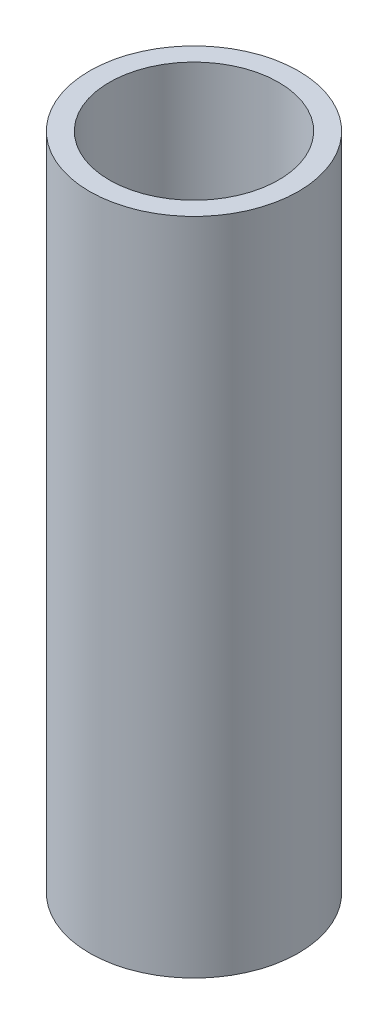
SolidWorks part; units mm, degrees
ref_plane "Front Plane" through (0, 0, 0) normal (0, 0, 1) x (1, 0, 0)
ref_plane "Top Plane" through (0, 0, 0) normal (0, 1, 0) x (1, 0, 0)
ref_plane "Right Plane" through (0, 0, 0) normal (1, 0, 0) x (0, 0, -1)
sketch "Sketch1" plane through (0, 0, 0) normal (0, 1, 0) x (1, 0, 0)
  circle A0 centre (0, 0) radius 2.375
  circle A1 centre (0, 0) radius 1.925
  dimension "D1" = 3.85
  dimension "D2" = 4.75
extrude "Boss-Extrude1" add sketch "Sketch1" along normal blind 15
